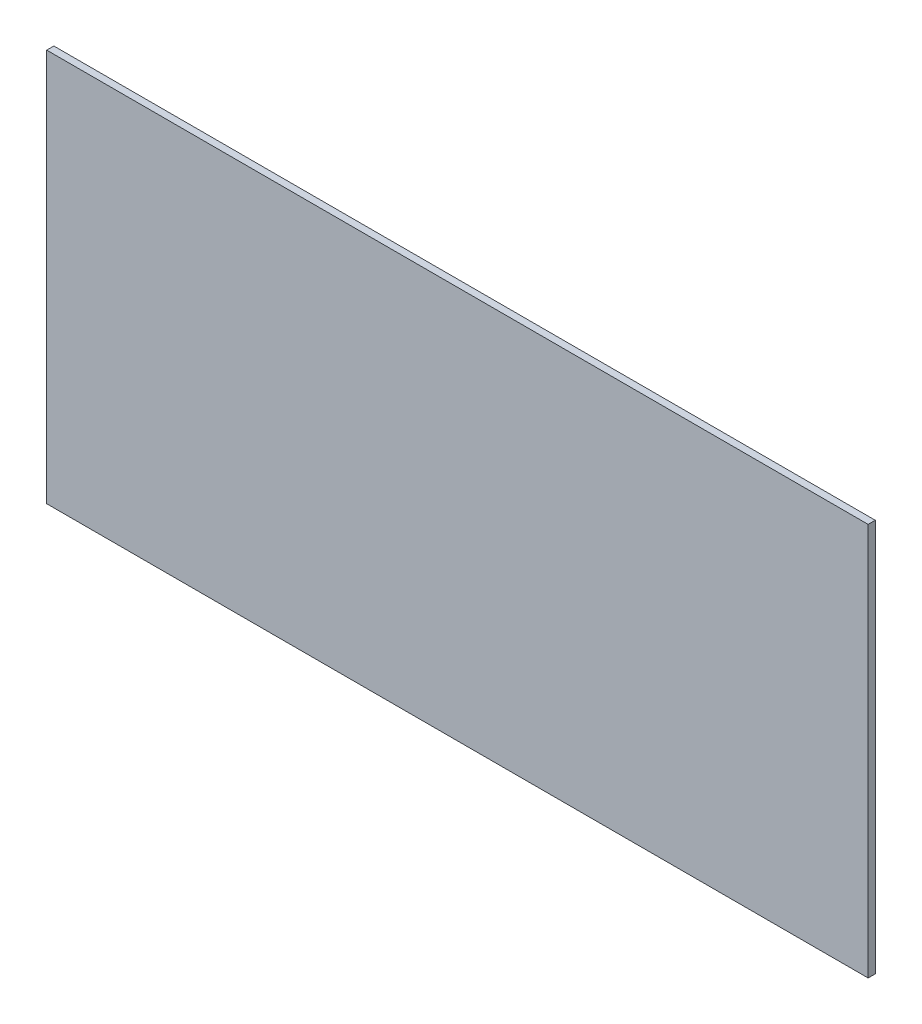
SolidWorks part; units mm, degrees
ref_plane "Front Plane" through (0, 0, 0) normal (0, 0, 1) x (1, 0, 0)
ref_plane "Top Plane" through (0, 0, 0) normal (0, 1, 0) x (1, 0, 0)
ref_plane "Right Plane" through (0, 0, 0) normal (1, 0, 0) x (0, 0, -1)
sketch "Sketch1" plane through (0, 0, 0) normal (0, 0, 1) x (1, 0, 0)
  line L1 (-218.2902, 94.8964) -> (11.7098, 94.8964)
  line L2 (-218.2902, 94.8964) -> (-218.2902, -15.1036)
  line L3 (-218.2902, -15.1036) -> (11.7098, -15.1036)
  line L4 (11.7098, 94.8964) -> (11.7098, -15.1036)
  dimension "D1" = 110
  dimension "D2" = 230
extrude "Boss-Extrude1" add sketch "Sketch1" along normal blind 2
